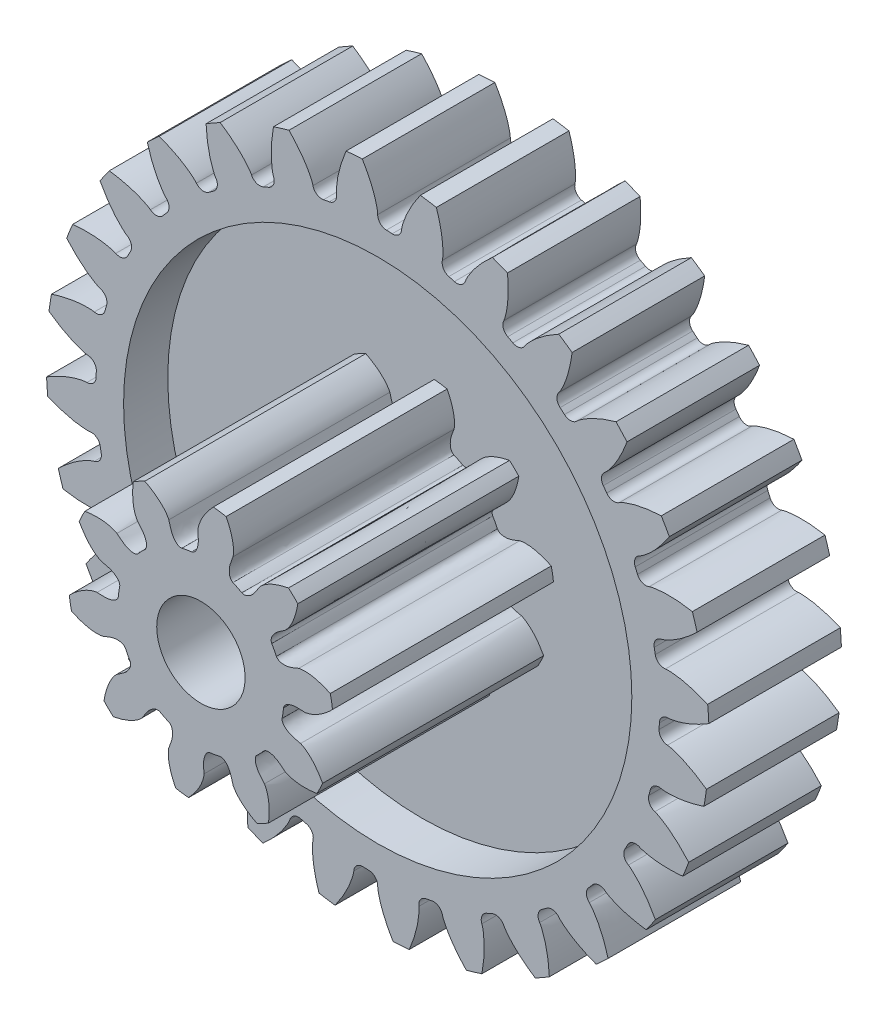
SolidWorks part; units mm, degrees
ref_plane "Plan de face" through (0, 0, 0) normal (0, 0, 1) x (1, 0, 0)
ref_plane "Plan de dessus" through (0, 0, 0) normal (0, 1, 0) x (1, 0, 0)
ref_plane "Plan de droite" through (0, 0, 0) normal (1, 0, 0) x (0, 0, -1)
sketch "Esquisse1" plane through (0, 0, 0) normal (0, 0, 1) x (1, 0, 0)
  arc A0 (7.4919, 0.3492) -> (7.4659, 0.7148) centre (0, 0) ccw
  arc A1 (7.2263, 2.0075) -> (7.1196, 2.3582) centre (0, 0) ccw
  arc A2 (6.5984, 3.5652) -> (6.4164, 3.8833) centre (0, 0) ccw
  arc A3 (5.6397, 4.9441) -> (5.3914, 5.2137) centre (0, 0) ccw
  arc A4 (4.3981, 6.0751) -> (4.0961, 6.2827) centre (0, 0) ccw
  arc A5 (2.936, 6.9014) -> (2.5953, 7.0366) centre (0, 0) ccw
  arc A6 (1.3267, 7.3817) -> (0.9645, 7.4377) centre (0, 0) ccw
  arc A7 (-0.3492, 7.4919) -> (-0.7148, 7.4659) centre (0, 0) ccw
  arc A8 (-2.0075, 7.2263) -> (-2.3582, 7.1196) centre (0, 0) ccw
  arc A9 (-3.5652, 6.5984) -> (-3.8833, 6.4164) centre (0, 0) ccw
  arc A10 (-4.9441, 5.6397) -> (-5.2137, 5.3914) centre (0, 0) ccw
  arc A11 (-6.0751, 4.3981) -> (-6.2827, 4.0961) centre (0, 0) ccw
  arc A12 (-6.9014, 2.936) -> (-7.0366, 2.5953) centre (0, 0) ccw
  arc A13 (-7.3817, 1.3267) -> (-7.4377, 0.9645) centre (0, 0) ccw
  arc A14 (-7.4919, -0.3492) -> (-7.4659, -0.7148) centre (0, 0) ccw
  arc A15 (-7.2263, -2.0075) -> (-7.1196, -2.3582) centre (0, 0) ccw
  arc A16 (-6.5984, -3.5652) -> (-6.4164, -3.8833) centre (0, 0) ccw
  arc A17 (-5.6397, -4.9441) -> (-5.3914, -5.2137) centre (0, 0) ccw
  arc A18 (-4.3981, -6.0751) -> (-4.0961, -6.2827) centre (0, 0) ccw
  arc A19 (-2.936, -6.9014) -> (-2.5953, -7.0366) centre (0, 0) ccw
  arc A20 (-1.3267, -7.3817) -> (-0.9645, -7.4377) centre (0, 0) ccw
  arc A21 (0.3492, -7.4919) -> (0.7148, -7.4659) centre (0, 0) ccw
  arc A22 (2.0075, -7.2263) -> (2.3582, -7.1196) centre (0, 0) ccw
  arc A23 (3.5652, -6.5984) -> (3.8833, -6.4164) centre (0, 0) ccw
  arc A24 (4.9441, -5.6397) -> (5.2137, -5.3914) centre (0, 0) ccw
  arc A25 (6.0751, -4.3981) -> (6.2827, -4.0961) centre (0, 0) ccw
  arc A26 (6.9014, -2.936) -> (7.0366, -2.5953) centre (0, 0) ccw
  arc A27 (7.3817, -1.3267) -> (7.4377, -0.9645) centre (0, 0) ccw
  arc A28 (6.578, 0) -> (6.372, -0.1967) centre (6.5749, -0.203) ccw
  arc A29 (6.3665, -0.3283) -> (6.5557, -0.5413) centre (6.5693, -0.3388) ccw
  arc A30 (6.3665, -0.3283) -> (6.372, -0.1967) centre (0, 0) ccw
  arc A31 (6.4131, 1.4637) -> (6.256, 1.2261) centre (6.4552, 1.2652) ccw
  arc A32 (6.28, 1.0966) -> (6.5118, 0.9311) centre (6.4799, 1.1315) ccw
  arc A33 (6.28, 1.0966) -> (6.256, 1.2261) centre (0, 0) ccw
  arc A34 (5.9266, 2.8541) -> (5.8263, 2.5875) centre (6.0118, 2.6699) ccw
  arc A35 (5.8785, 2.4666) -> (6.1413, 2.3567) centre (6.0657, 2.5451) ccw
  arc A36 (5.8785, 2.4666) -> (5.8263, 2.5875) centre (0, 0) ccw
  arc A37 (5.1429, 4.1013) -> (5.1045, 3.8191) centre (5.267, 3.9407) ccw
  arc A38 (5.1823, 3.7128) -> (5.4629, 3.6642) centre (5.3473, 3.831) ccw
  arc A39 (5.1823, 3.7128) -> (5.1045, 3.8191) centre (0, 0) ccw
  arc A40 (4.1013, 5.1429) -> (4.1267, 4.8592) centre (4.2581, 5.0139) ccw
  arc A41 (4.2261, 4.7729) -> (4.5106, 4.788) centre (4.3607, 4.9249) ccw
  arc A42 (4.2261, 4.7729) -> (4.1267, 4.8592) centre (0, 0) ccw
  arc A43 (2.8541, 5.9266) -> (2.9419, 5.6556) centre (3.0356, 5.8357) ccw
  arc A44 (3.0581, 5.5936) -> (3.3321, 5.6716) centre (3.1555, 5.7717) ccw
  arc A45 (3.0581, 5.5936) -> (2.9419, 5.6556) centre (0, 0) ccw
  arc A46 (1.4637, 6.4131) -> (1.6097, 6.1684) centre (1.6609, 6.3649) ccw
  arc A47 (1.7368, 6.1339) -> (1.9865, 6.2709) centre (1.7921, 6.3292) ccw
  arc A48 (1.7368, 6.1339) -> (1.6097, 6.1684) centre (0, 0) ccw
  arc A49 (0, 6.578) -> (0.1967, 6.372) centre (0.203, 6.5749) ccw
  arc A50 (0.3283, 6.3665) -> (0.5413, 6.5557) centre (0.3388, 6.5693) ccw
  arc A51 (0.3283, 6.3665) -> (0.1967, 6.372) centre (0, 0) ccw
  arc A52 (-1.4637, 6.4131) -> (-1.2261, 6.256) centre (-1.2652, 6.4552) ccw
  arc A53 (-1.0966, 6.28) -> (-0.9311, 6.5118) centre (-1.1315, 6.4799) ccw
  arc A54 (-1.0966, 6.28) -> (-1.2261, 6.256) centre (0, 0) ccw
  arc A55 (-2.8541, 5.9266) -> (-2.5875, 5.8263) centre (-2.6699, 6.0118) ccw
  arc A56 (-2.4666, 5.8785) -> (-2.3567, 6.1413) centre (-2.5451, 6.0657) ccw
  arc A57 (-2.4666, 5.8785) -> (-2.5875, 5.8263) centre (0, 0) ccw
  arc A58 (-4.1013, 5.1429) -> (-3.8191, 5.1045) centre (-3.9407, 5.267) ccw
  arc A59 (-3.7128, 5.1823) -> (-3.6642, 5.4629) centre (-3.831, 5.3473) ccw
  arc A60 (-3.7128, 5.1823) -> (-3.8191, 5.1045) centre (0, 0) ccw
  arc A61 (-5.1429, 4.1013) -> (-4.8592, 4.1267) centre (-5.0139, 4.2581) ccw
  arc A62 (-4.7729, 4.2261) -> (-4.788, 4.5106) centre (-4.9249, 4.3607) ccw
  arc A63 (-4.7729, 4.2261) -> (-4.8592, 4.1267) centre (0, 0) ccw
  arc A64 (-5.9266, 2.8541) -> (-5.6556, 2.9419) centre (-5.8357, 3.0356) ccw
  arc A65 (-5.5936, 3.0581) -> (-5.6716, 3.3321) centre (-5.7717, 3.1555) ccw
  arc A66 (-5.5936, 3.0581) -> (-5.6556, 2.9419) centre (0, 0) ccw
  arc A67 (-6.4131, 1.4637) -> (-6.1684, 1.6097) centre (-6.3649, 1.6609) ccw
  arc A68 (-6.1339, 1.7368) -> (-6.2709, 1.9865) centre (-6.3292, 1.7921) ccw
  arc A69 (-6.1339, 1.7368) -> (-6.1684, 1.6097) centre (0, 0) ccw
  arc A70 (-6.578, 0) -> (-6.372, 0.1967) centre (-6.5749, 0.203) ccw
  arc A71 (-6.3665, 0.3283) -> (-6.5557, 0.5413) centre (-6.5693, 0.3388) ccw
  arc A72 (-6.3665, 0.3283) -> (-6.372, 0.1967) centre (0, 0) ccw
  arc A73 (-6.4131, -1.4637) -> (-6.256, -1.2261) centre (-6.4552, -1.2652) ccw
  arc A74 (-6.28, -1.0966) -> (-6.5118, -0.9311) centre (-6.4799, -1.1315) ccw
  arc A75 (-6.28, -1.0966) -> (-6.256, -1.2261) centre (0, 0) ccw
  arc A76 (-5.9266, -2.8541) -> (-5.8263, -2.5875) centre (-6.0118, -2.6699) ccw
  arc A77 (-5.8785, -2.4666) -> (-6.1413, -2.3567) centre (-6.0657, -2.5451) ccw
  arc A78 (-5.8785, -2.4666) -> (-5.8263, -2.5875) centre (0, 0) ccw
  arc A79 (-5.1429, -4.1013) -> (-5.1045, -3.8191) centre (-5.267, -3.9407) ccw
  arc A80 (-5.1823, -3.7128) -> (-5.4629, -3.6642) centre (-5.3473, -3.831) ccw
  arc A81 (-5.1823, -3.7128) -> (-5.1045, -3.8191) centre (0, 0) ccw
  arc A82 (-4.1013, -5.1429) -> (-4.1267, -4.8592) centre (-4.2581, -5.0139) ccw
  arc A83 (-4.2261, -4.7729) -> (-4.5106, -4.788) centre (-4.3607, -4.9249) ccw
  arc A84 (-4.2261, -4.7729) -> (-4.1267, -4.8592) centre (0, 0) ccw
  arc A85 (-2.8541, -5.9266) -> (-2.9419, -5.6556) centre (-3.0356, -5.8357) ccw
  arc A86 (-3.0581, -5.5936) -> (-3.3321, -5.6716) centre (-3.1555, -5.7717) ccw
  arc A87 (-3.0581, -5.5936) -> (-2.9419, -5.6556) centre (0, 0) ccw
  arc A88 (-1.4637, -6.4131) -> (-1.6097, -6.1684) centre (-1.6609, -6.3649) ccw
  arc A89 (-1.7368, -6.1339) -> (-1.9865, -6.2709) centre (-1.7921, -6.3292) ccw
  arc A90 (-1.7368, -6.1339) -> (-1.6097, -6.1684) centre (0, 0) ccw
  arc A91 (0, -6.578) -> (-0.1967, -6.372) centre (-0.203, -6.5749) ccw
  arc A92 (-0.3283, -6.3665) -> (-0.5413, -6.5557) centre (-0.3388, -6.5693) ccw
  arc A93 (-0.3283, -6.3665) -> (-0.1967, -6.372) centre (0, 0) ccw
  arc A94 (1.4637, -6.4131) -> (1.2261, -6.256) centre (1.2652, -6.4552) ccw
  arc A95 (1.0966, -6.28) -> (0.9311, -6.5118) centre (1.1315, -6.4799) ccw
  arc A96 (1.0966, -6.28) -> (1.2261, -6.256) centre (0, 0) ccw
  arc A97 (2.8541, -5.9266) -> (2.5875, -5.8263) centre (2.6699, -6.0118) ccw
  arc A98 (2.4666, -5.8785) -> (2.3567, -6.1413) centre (2.5451, -6.0657) ccw
  arc A99 (2.4666, -5.8785) -> (2.5875, -5.8263) centre (0, 0) ccw
  arc A100 (4.1013, -5.1429) -> (3.8191, -5.1045) centre (3.9407, -5.267) ccw
  arc A101 (3.7128, -5.1823) -> (3.6642, -5.4629) centre (3.831, -5.3473) ccw
  arc A102 (3.7128, -5.1823) -> (3.8191, -5.1045) centre (0, 0) ccw
  arc A103 (5.1429, -4.1013) -> (4.8592, -4.1267) centre (5.0139, -4.2581) ccw
  arc A104 (4.7729, -4.2261) -> (4.788, -4.5106) centre (4.9249, -4.3607) ccw
  arc A105 (4.7729, -4.2261) -> (4.8592, -4.1267) centre (0, 0) ccw
  arc A106 (5.9266, -2.8541) -> (5.6556, -2.9419) centre (5.8357, -3.0356) ccw
  arc A107 (5.5936, -3.0581) -> (5.6716, -3.3321) centre (5.7717, -3.1555) ccw
  arc A108 (5.5936, -3.0581) -> (5.6556, -2.9419) centre (0, 0) ccw
  arc A109 (6.4131, -1.4637) -> (6.1684, -1.6097) centre (6.3649, -1.6609) ccw
  arc A110 (6.1339, -1.7368) -> (6.2709, -1.9865) centre (6.3292, -1.7921) ccw
  arc A111 (6.1339, -1.7368) -> (6.1684, -1.6097) centre (0, 0) ccw
  circle A112 centre (0, 0) radius 1
  spline S0 degree 3 poles (6.578, 0) (6.6119, 0) (6.7559, 0.0236) (6.9849, 0.0917) (7.2537, 0.2125) (7.4145, 0.3021) (7.4919, 0.3492) knots 0 0 0 0 0.1017 0.434977 0.714423 0.984887 0.984887 0.984887 0.984887
  spline S1 degree 3 poles (6.5118, 0.9311) (6.5453, 0.9359) (6.6912, 0.9329) (6.9276, 0.8979) (7.2108, 0.8163) (7.3826, 0.7504) (7.4659, 0.7148) knots 0 0 0 0 0.1017 0.434977 0.714423 0.984887 0.984887 0.984887 0.984887
  spline S2 degree 3 poles (6.4131, 1.4637) (6.4461, 1.4713) (6.5813, 1.5263) (6.7894, 1.6437) (7.0245, 1.8213) (7.1614, 1.9444) (7.2263, 2.0075) knots 0 0 0 0 0.1017 0.434977 0.714423 0.984887 0.984887 0.984887 0.984887
  spline S3 degree 3 poles (6.1413, 2.3567) (6.173, 2.3689) (6.3159, 2.3984) (6.5541, 2.4169) (6.8483, 2.4004) (7.0306, 2.3743) (7.1196, 2.3582) knots 0 0 0 0 0.1017 0.434977 0.714423 0.984887 0.984887 0.984887 0.984887
  spline S4 degree 3 poles (5.9266, 2.8541) (5.9571, 2.8688) (6.0766, 2.9525) (6.2534, 3.1132) (6.4431, 3.3388) (6.5492, 3.4892) (6.5984, 3.5652) knots 0 0 0 0 0.1017 0.434977 0.714423 0.984887 0.984887 0.984887 0.984887
  spline S5 degree 3 poles (5.4629, 3.6642) (5.4911, 3.6831) (5.6238, 3.7437) (5.8519, 3.8147) (6.1425, 3.8641) (6.3259, 3.8793) (6.4164, 3.8833) knots 0 0 0 0 0.1017 0.434977 0.714423 0.984887 0.984887 0.984887 0.984887
  spline S6 degree 3 poles (5.1429, 4.1013) (5.1694, 4.1225) (5.2673, 4.2307) (5.4039, 4.4267) (5.5387, 4.6888) (5.6085, 4.8591) (5.6397, 4.9441) knots 0 0 0 0 0.1017 0.434977 0.714423 0.984887 0.984887 0.984887 0.984887
  spline S7 degree 3 poles (4.5106, 4.788) (4.5339, 4.8126) (4.6498, 4.9013) (4.8563, 5.0213) (5.1286, 5.134) (5.3041, 5.1897) (5.3914, 5.2137) knots 0 0 0 0 0.1017 0.434977 0.714423 0.984887 0.984887 0.984887 0.984887
  spline S8 degree 3 poles (4.1013, 5.1429) (4.1225, 5.1694) (4.1938, 5.2967) (4.2833, 5.5182) (4.3564, 5.8037) (4.3867, 5.9853) (4.3981, 6.0751) knots 0 0 0 0 0.1017 0.434977 0.714423 0.984887 0.984887 0.984887 0.984887
  spline S9 degree 3 poles (3.3321, 5.6716) (3.3493, 5.7008) (3.4426, 5.8131) (3.6173, 5.976) (3.8576, 6.1465) (4.0163, 6.2398) (4.0961, 6.2827) knots 0 0 0 0 0.1017 0.434977 0.714423 0.984887 0.984887 0.984887 0.984887
  spline S10 degree 3 poles (2.8541, 5.9266) (2.8688, 5.9571) (2.91, 6.0971) (2.948, 6.333) (2.9558, 6.6276) (2.9448, 6.8113) (2.936, 6.9014) knots 0 0 0 0 0.1017 0.434977 0.714423 0.984887 0.984887 0.984887 0.984887
  spline S11 degree 3 poles (1.9865, 6.2709) (1.9967, 6.3032) (2.0627, 6.4334) (2.1968, 6.6311) (2.3932, 6.8508) (2.5271, 6.9771) (2.5953, 7.0366) knots 0 0 0 0 0.1017 0.434977 0.714423 0.984887 0.984887 0.984887 0.984887
  spline S12 degree 3 poles (1.4637, 6.4131) (1.4713, 6.4461) (1.4803, 6.5918) (1.4649, 6.8302) (1.4069, 7.1191) (1.3553, 7.2958) (1.3267, 7.3817) knots 0 0 0 0 0.1017 0.434977 0.714423 0.984887 0.984887 0.984887 0.984887
  spline S13 degree 3 poles (0.5413, 6.5557) (0.5441, 6.5895) (0.5794, 6.7311) (0.6661, 6.9537) (0.8087, 7.2116) (0.9112, 7.3645) (0.9645, 7.4377) knots 0 0 0 0 0.1017 0.434977 0.714423 0.984887 0.984887 0.984887 0.984887
  spline S14 degree 3 poles (0, 6.578) (0, 6.6119) (-0.0236, 6.7559) (-0.0917, 6.9849) (-0.2125, 7.2537) (-0.3021, 7.4145) (-0.3492, 7.4919) knots 0 0 0 0 0.1017 0.434977 0.714423 0.984887 0.984887 0.984887 0.984887
  spline S15 degree 3 poles (-0.9311, 6.5118) (-0.9359, 6.5453) (-0.9329, 6.6912) (-0.8979, 6.9276) (-0.8163, 7.2108) (-0.7504, 7.3826) (-0.7148, 7.4659) knots 0 0 0 0 0.1017 0.434977 0.714423 0.984887 0.984887 0.984887 0.984887
  spline S16 degree 3 poles (-1.4637, 6.4131) (-1.4713, 6.4461) (-1.5263, 6.5813) (-1.6437, 6.7894) (-1.8213, 7.0245) (-1.9444, 7.1614) (-2.0075, 7.2263) knots 0 0 0 0 0.1017 0.434977 0.714423 0.984887 0.984887 0.984887 0.984887
  spline S17 degree 3 poles (-2.3567, 6.1413) (-2.3689, 6.173) (-2.3984, 6.3159) (-2.4169, 6.5541) (-2.4004, 6.8483) (-2.3743, 7.0306) (-2.3582, 7.1196) knots 0 0 0 0 0.1017 0.434977 0.714423 0.984887 0.984887 0.984887 0.984887
  spline S18 degree 3 poles (-2.8541, 5.9266) (-2.8688, 5.9571) (-2.9525, 6.0766) (-3.1132, 6.2534) (-3.3388, 6.4431) (-3.4892, 6.5492) (-3.5652, 6.5984) knots 0 0 0 0 0.1017 0.434977 0.714423 0.984887 0.984887 0.984887 0.984887
  spline S19 degree 3 poles (-3.6642, 5.4629) (-3.6831, 5.4911) (-3.7437, 5.6238) (-3.8147, 5.8519) (-3.8641, 6.1425) (-3.8793, 6.3259) (-3.8833, 6.4164) knots 0 0 0 0 0.1017 0.434977 0.714423 0.984887 0.984887 0.984887 0.984887
  spline S20 degree 3 poles (-4.1013, 5.1429) (-4.1225, 5.1694) (-4.2307, 5.2673) (-4.4267, 5.4039) (-4.6888, 5.5387) (-4.8591, 5.6085) (-4.9441, 5.6397) knots 0 0 0 0 0.1017 0.434977 0.714423 0.984887 0.984887 0.984887 0.984887
  spline S21 degree 3 poles (-4.788, 4.5106) (-4.8126, 4.5339) (-4.9013, 4.6498) (-5.0213, 4.8563) (-5.134, 5.1286) (-5.1897, 5.3041) (-5.2137, 5.3914) knots 0 0 0 0 0.1017 0.434977 0.714423 0.984887 0.984887 0.984887 0.984887
  spline S22 degree 3 poles (-5.1429, 4.1013) (-5.1694, 4.1225) (-5.2967, 4.1938) (-5.5182, 4.2833) (-5.8037, 4.3564) (-5.9853, 4.3867) (-6.0751, 4.3981) knots 0 0 0 0 0.1017 0.434977 0.714423 0.984887 0.984887 0.984887 0.984887
  spline S23 degree 3 poles (-5.6716, 3.3321) (-5.7008, 3.3493) (-5.8131, 3.4426) (-5.976, 3.6173) (-6.1465, 3.8576) (-6.2398, 4.0163) (-6.2827, 4.0961) knots 0 0 0 0 0.1017 0.434977 0.714423 0.984887 0.984887 0.984887 0.984887
  spline S24 degree 3 poles (-5.9266, 2.8541) (-5.9571, 2.8688) (-6.0971, 2.91) (-6.333, 2.948) (-6.6276, 2.9558) (-6.8113, 2.9448) (-6.9014, 2.936) knots 0 0 0 0 0.1017 0.434977 0.714423 0.984887 0.984887 0.984887 0.984887
  spline S25 degree 3 poles (-6.2709, 1.9865) (-6.3032, 1.9967) (-6.4334, 2.0627) (-6.6311, 2.1968) (-6.8508, 2.3932) (-6.9771, 2.5271) (-7.0366, 2.5953) knots 0 0 0 0 0.1017 0.434977 0.714423 0.984887 0.984887 0.984887 0.984887
  spline S26 degree 3 poles (-6.4131, 1.4637) (-6.4461, 1.4713) (-6.5918, 1.4803) (-6.8302, 1.4649) (-7.1191, 1.4069) (-7.2958, 1.3553) (-7.3817, 1.3267) knots 0 0 0 0 0.1017 0.434977 0.714423 0.984887 0.984887 0.984887 0.984887
  spline S27 degree 3 poles (-6.5557, 0.5413) (-6.5895, 0.5441) (-6.7311, 0.5794) (-6.9537, 0.6661) (-7.2116, 0.8087) (-7.3645, 0.9112) (-7.4377, 0.9645) knots 0 0 0 0 0.1017 0.434977 0.714423 0.984887 0.984887 0.984887 0.984887
  spline S28 degree 3 poles (-6.578, 0) (-6.6119, 0) (-6.7559, -0.0236) (-6.9849, -0.0917) (-7.2537, -0.2125) (-7.4145, -0.3021) (-7.4919, -0.3492) knots 0 0 0 0 0.1017 0.434977 0.714423 0.984887 0.984887 0.984887 0.984887
  spline S29 degree 3 poles (-6.5118, -0.9311) (-6.5453, -0.9359) (-6.6912, -0.9329) (-6.9276, -0.8979) (-7.2108, -0.8163) (-7.3826, -0.7504) (-7.4659, -0.7148) knots 0 0 0 0 0.1017 0.434977 0.714423 0.984887 0.984887 0.984887 0.984887
  spline S30 degree 3 poles (-6.4131, -1.4637) (-6.4461, -1.4713) (-6.5813, -1.5263) (-6.7894, -1.6437) (-7.0245, -1.8213) (-7.1614, -1.9444) (-7.2263, -2.0075) knots 0 0 0 0 0.1017 0.434977 0.714423 0.984887 0.984887 0.984887 0.984887
  spline S31 degree 3 poles (-6.1413, -2.3567) (-6.173, -2.3689) (-6.3159, -2.3984) (-6.5541, -2.4169) (-6.8483, -2.4004) (-7.0306, -2.3743) (-7.1196, -2.3582) knots 0 0 0 0 0.1017 0.434977 0.714423 0.984887 0.984887 0.984887 0.984887
  spline S32 degree 3 poles (-5.9266, -2.8541) (-5.9571, -2.8688) (-6.0766, -2.9525) (-6.2534, -3.1132) (-6.4431, -3.3388) (-6.5492, -3.4892) (-6.5984, -3.5652) knots 0 0 0 0 0.1017 0.434977 0.714423 0.984887 0.984887 0.984887 0.984887
  spline S33 degree 3 poles (-5.4629, -3.6642) (-5.4911, -3.6831) (-5.6238, -3.7437) (-5.8519, -3.8147) (-6.1425, -3.8641) (-6.3259, -3.8793) (-6.4164, -3.8833) knots 0 0 0 0 0.1017 0.434977 0.714423 0.984887 0.984887 0.984887 0.984887
  spline S34 degree 3 poles (-5.1429, -4.1013) (-5.1694, -4.1225) (-5.2673, -4.2307) (-5.4039, -4.4267) (-5.5387, -4.6888) (-5.6085, -4.8591) (-5.6397, -4.9441) knots 0 0 0 0 0.1017 0.434977 0.714423 0.984887 0.984887 0.984887 0.984887
  spline S35 degree 3 poles (-4.5106, -4.788) (-4.5339, -4.8126) (-4.6498, -4.9013) (-4.8563, -5.0213) (-5.1286, -5.134) (-5.3041, -5.1897) (-5.3914, -5.2137) knots 0 0 0 0 0.1017 0.434977 0.714423 0.984887 0.984887 0.984887 0.984887
  spline S36 degree 3 poles (-4.1013, -5.1429) (-4.1225, -5.1694) (-4.1938, -5.2967) (-4.2833, -5.5182) (-4.3564, -5.8037) (-4.3867, -5.9853) (-4.3981, -6.0751) knots 0 0 0 0 0.1017 0.434977 0.714423 0.984887 0.984887 0.984887 0.984887
  spline S37 degree 3 poles (-3.3321, -5.6716) (-3.3493, -5.7008) (-3.4426, -5.8131) (-3.6173, -5.976) (-3.8576, -6.1465) (-4.0163, -6.2398) (-4.0961, -6.2827) knots 0 0 0 0 0.1017 0.434977 0.714423 0.984887 0.984887 0.984887 0.984887
  spline S38 degree 3 poles (-2.8541, -5.9266) (-2.8688, -5.9571) (-2.91, -6.0971) (-2.948, -6.333) (-2.9558, -6.6276) (-2.9448, -6.8113) (-2.936, -6.9014) knots 0 0 0 0 0.1017 0.434977 0.714423 0.984887 0.984887 0.984887 0.984887
  spline S39 degree 3 poles (-1.9865, -6.2709) (-1.9967, -6.3032) (-2.0627, -6.4334) (-2.1968, -6.6311) (-2.3932, -6.8508) (-2.5271, -6.9771) (-2.5953, -7.0366) knots 0 0 0 0 0.1017 0.434977 0.714423 0.984887 0.984887 0.984887 0.984887
  spline S40 degree 3 poles (-1.4637, -6.4131) (-1.4713, -6.4461) (-1.4803, -6.5918) (-1.4649, -6.8302) (-1.4069, -7.1191) (-1.3553, -7.2958) (-1.3267, -7.3817) knots 0 0 0 0 0.1017 0.434977 0.714423 0.984887 0.984887 0.984887 0.984887
  spline S41 degree 3 poles (-0.5413, -6.5557) (-0.5441, -6.5895) (-0.5794, -6.7311) (-0.6661, -6.9537) (-0.8087, -7.2116) (-0.9112, -7.3645) (-0.9645, -7.4377) knots 0 0 0 0 0.1017 0.434977 0.714423 0.984887 0.984887 0.984887 0.984887
  spline S42 degree 3 poles (0, -6.578) (0, -6.6119) (0.0236, -6.7559) (0.0917, -6.9849) (0.2125, -7.2537) (0.3021, -7.4145) (0.3492, -7.4919) knots 0 0 0 0 0.1017 0.434977 0.714423 0.984887 0.984887 0.984887 0.984887
  spline S43 degree 3 poles (0.9311, -6.5118) (0.9359, -6.5453) (0.9329, -6.6912) (0.8979, -6.9276) (0.8163, -7.2108) (0.7504, -7.3826) (0.7148, -7.4659) knots 0 0 0 0 0.1017 0.434977 0.714423 0.984887 0.984887 0.984887 0.984887
  spline S44 degree 3 poles (1.4637, -6.4131) (1.4713, -6.4461) (1.5263, -6.5813) (1.6437, -6.7894) (1.8213, -7.0245) (1.9444, -7.1614) (2.0075, -7.2263) knots 0 0 0 0 0.1017 0.434977 0.714423 0.984887 0.984887 0.984887 0.984887
  spline S45 degree 3 poles (2.3567, -6.1413) (2.3689, -6.173) (2.3984, -6.3159) (2.4169, -6.5541) (2.4004, -6.8483) (2.3743, -7.0306) (2.3582, -7.1196) knots 0 0 0 0 0.1017 0.434977 0.714423 0.984887 0.984887 0.984887 0.984887
  spline S46 degree 3 poles (2.8541, -5.9266) (2.8688, -5.9571) (2.9525, -6.0766) (3.1132, -6.2534) (3.3388, -6.4431) (3.4892, -6.5492) (3.5652, -6.5984) knots 0 0 0 0 0.1017 0.434977 0.714423 0.984887 0.984887 0.984887 0.984887
  spline S47 degree 3 poles (3.6642, -5.4629) (3.6831, -5.4911) (3.7437, -5.6238) (3.8147, -5.8519) (3.8641, -6.1425) (3.8793, -6.3259) (3.8833, -6.4164) knots 0 0 0 0 0.1017 0.434977 0.714423 0.984887 0.984887 0.984887 0.984887
  spline S48 degree 3 poles (4.1013, -5.1429) (4.1225, -5.1694) (4.2307, -5.2673) (4.4267, -5.4039) (4.6888, -5.5387) (4.8591, -5.6085) (4.9441, -5.6397) knots 0 0 0 0 0.1017 0.434977 0.714423 0.984887 0.984887 0.984887 0.984887
  spline S49 degree 3 poles (4.788, -4.5106) (4.8126, -4.5339) (4.9013, -4.6498) (5.0213, -4.8563) (5.134, -5.1286) (5.1897, -5.3041) (5.2137, -5.3914) knots 0 0 0 0 0.1017 0.434977 0.714423 0.984887 0.984887 0.984887 0.984887
  spline S50 degree 3 poles (5.1429, -4.1013) (5.1694, -4.1225) (5.2967, -4.1938) (5.5182, -4.2833) (5.8037, -4.3564) (5.9853, -4.3867) (6.0751, -4.3981) knots 0 0 0 0 0.1017 0.434977 0.714423 0.984887 0.984887 0.984887 0.984887
  spline S51 degree 3 poles (5.6716, -3.3321) (5.7008, -3.3493) (5.8131, -3.4426) (5.976, -3.6173) (6.1465, -3.8576) (6.2398, -4.0163) (6.2827, -4.0961) knots 0 0 0 0 0.1017 0.434977 0.714423 0.984887 0.984887 0.984887 0.984887
  spline S52 degree 3 poles (5.9266, -2.8541) (5.9571, -2.8688) (6.0971, -2.91) (6.333, -2.948) (6.6276, -2.9558) (6.8113, -2.9448) (6.9014, -2.936) knots 0 0 0 0 0.1017 0.434977 0.714423 0.984887 0.984887 0.984887 0.984887
  spline S53 degree 3 poles (6.2709, -1.9865) (6.3032, -1.9967) (6.4334, -2.0627) (6.6311, -2.1968) (6.8508, -2.3932) (6.9771, -2.5271) (7.0366, -2.5953) knots 0 0 0 0 0.1017 0.434977 0.714423 0.984887 0.984887 0.984887 0.984887
  spline S54 degree 3 poles (6.4131, -1.4637) (6.4461, -1.4713) (6.5918, -1.4803) (6.8302, -1.4649) (7.1191, -1.4069) (7.2958, -1.3553) (7.3817, -1.3267) knots 0 0 0 0 0.1017 0.434977 0.714423 0.984887 0.984887 0.984887 0.984887
  spline S55 degree 3 poles (6.5557, -0.5413) (6.5895, -0.5441) (6.7311, -0.5794) (6.9537, -0.6661) (7.2116, -0.8087) (7.3645, -0.9112) (7.4377, -0.9645) knots 0 0 0 0 0.1017 0.434977 0.714423 0.984887 0.984887 0.984887 0.984887
  dimension "D1" = 2
extrude "Boss.-Extru.1" add sketch "Esquisse1" along normal blind 3
sketch "Esquisse2" plane through (0, 0, 3) normal (0, 0, 1) x (1, 0, 0)
  circle A0 centre (0, 0) radius 5.75
  dimension "D1" = 11.5
extrude "Enlèv. mat.-Extru.1" cut sketch "Esquisse2" against normal blind 1
sketch "Esquisse3" plane through (0, 0, 2) normal (0, 0, 1) x (1, 0, 0)
  arc A0 (2.9773, 0.3683) -> (2.9271, 0.6573) centre (0, 0) ccw
  arc A1 (2.1922, 2.048) -> (1.9817, 2.2523) centre (0, 0) ccw
  arc A2 (0.5698, 2.9454) -> (0.2794, 2.987) centre (0, 0) ccw
  arc A3 (-1.2703, 2.7178) -> (-1.5297, 2.5807) centre (0, 0) ccw
  arc A4 (-2.6252, 1.4521) -> (-2.7544, 1.1887) centre (0, 0) ccw
  arc A5 (-2.9773, -0.3683) -> (-2.9271, -0.6573) centre (0, 0) ccw
  arc A6 (-2.1922, -2.048) -> (-1.9817, -2.2523) centre (0, 0) ccw
  arc A7 (-0.5698, -2.9454) -> (-0.2794, -2.987) centre (0, 0) ccw
  arc A8 (1.2703, -2.7178) -> (1.5297, -2.5807) centre (0, 0) ccw
  arc A9 (2.6252, -1.4521) -> (2.7544, -1.1887) centre (0, 0) ccw
  arc A10 (1.8368, -0.3764) -> (1.8687, -0.154) centre (0, 0) ccw
  arc A11 (1.7073, 0.7751) -> (1.6023, 0.9738) centre (0, 0) ccw
  arc A12 (0.9256, 1.6306) -> (0.7239, 1.7296) centre (0, 0) ccw
  arc A13 (-0.2096, 1.8632) -> (-0.431, 1.8248) centre (0, 0) ccw
  arc A14 (-1.2648, 1.3842) -> (-1.4213, 1.2229) centre (0, 0) ccw
  arc A15 (-1.8368, 0.3764) -> (-1.8687, 0.154) centre (0, 0) ccw
  arc A16 (-1.7073, -0.7751) -> (-1.6023, -0.9738) centre (0, 0) ccw
  arc A17 (-0.9256, -1.6306) -> (-0.7239, -1.7296) centre (0, 0) ccw
  arc A18 (0.2096, -1.8632) -> (0.431, -1.8248) centre (0, 0) ccw
  arc A19 (1.2648, -1.3842) -> (1.4213, -1.2229) centre (0, 0) ccw
  circle A20 centre (0, 0) radius 1 construction
  circle A21 centre (0, 0) radius 1
  spline S0 degree 3 poles (2.349, 0) (2.3611, 0) (2.4126, 0.0085) (2.4945, 0.0326) (2.6584, 0.1065) (2.823, 0.2207) (2.9394, 0.3292) (2.9773, 0.3683) knots 0 0 0 0 0.036251 0.155621 0.255291 0.575255 0.744085 0.744085 0.744085 0.744085
  spline S1 degree 3 poles (2.2114, 0.7921) (2.2228, 0.7962) (2.2741, 0.8056) (2.3594, 0.8105) (2.5386, 0.7962) (2.7321, 0.7442) (2.8782, 0.6813) (2.9271, 0.6573) knots 0 0 0 0 0.036251 0.155621 0.255291 0.575255 0.744085 0.744085 0.744085 0.744085
  spline S2 degree 3 poles (1.9004, 1.3807) (1.9102, 1.3878) (1.9469, 1.4249) (1.9989, 1.4926) (2.0881, 1.6487) (2.1541, 1.8379) (2.1845, 1.9941) (2.1922, 2.048) knots 0 0 0 0 0.036251 0.155621 0.255291 0.575255 0.744085 0.744085 0.744085 0.744085
  spline S3 degree 3 poles (1.3235, 1.9407) (1.3303, 1.9507) (1.3663, 1.9885) (1.4324, 2.0425) (1.5858, 2.1363) (1.7728, 2.2079) (1.9281, 2.243) (1.9817, 2.2523) knots 0 0 0 0 0.036251 0.155621 0.255291 0.575255 0.744085 0.744085 0.744085 0.744085
  spline S4 degree 3 poles (0.7259, 2.234) (0.7296, 2.2455) (0.7375, 2.2971) (0.7398, 2.3825) (0.7202, 2.5612) (0.6625, 2.753) (0.5952, 2.8973) (0.5698, 2.9454) knots 0 0 0 0 0.036251 0.155621 0.255291 0.575255 0.744085 0.744085 0.744085 0.744085
  spline S5 degree 3 poles (-0.07, 2.348) (-0.0704, 2.36) (-0.0634, 2.4118) (-0.0417, 2.4943) (0.0272, 2.6604) (0.1365, 2.8283) (0.2415, 2.9479) (0.2794, 2.987) knots 0 0 0 0 0.036251 0.155621 0.255291 0.575255 0.744085 0.744085 0.744085 0.744085
  spline S6 degree 3 poles (-0.7259, 2.234) (-0.7296, 2.2455) (-0.7536, 2.2919) (-0.8019, 2.3623) (-0.9228, 2.4954) (-1.0823, 2.6166) (-1.2215, 2.6938) (-1.2703, 2.7178) knots 0 0 0 0 0.036251 0.155621 0.255291 0.575255 0.744085 0.744085 0.744085 0.744085
  spline S7 degree 3 poles (-1.4367, 1.8584) (-1.4441, 1.8679) (-1.4689, 1.9139) (-1.4999, 1.9934) (-1.5417, 2.1683) (-1.552, 2.3684) (-1.5374, 2.5268) (-1.5297, 2.5807) knots 0 0 0 0 0.036251 0.155621 0.255291 0.575255 0.744085 0.744085 0.744085 0.744085
  spline S8 degree 3 poles (-1.9004, 1.3807) (-1.9102, 1.3878) (-1.9568, 1.4112) (-2.0373, 1.4398) (-2.2133, 1.4764) (-2.4136, 1.4808) (-2.5715, 1.4614) (-2.6252, 1.4521) knots 0 0 0 0 0.036251 0.155621 0.255291 0.575255 0.744085 0.744085 0.744085 0.744085
  spline S9 degree 3 poles (-2.2547, 0.659) (-2.2663, 0.6624) (-2.3133, 0.6849) (-2.3852, 0.7311) (-2.5218, 0.848) (-2.6477, 1.0038) (-2.729, 1.1406) (-2.7544, 1.1887) knots 0 0 0 0 0.036251 0.155621 0.255291 0.575255 0.744085 0.744085 0.744085 0.744085
  spline S10 degree 3 poles (-2.349, 0) (-2.3611, 0) (-2.4126, -0.0085) (-2.4945, -0.0326) (-2.6584, -0.1065) (-2.823, -0.2207) (-2.9394, -0.3292) (-2.9773, -0.3683) knots 0 0 0 0 0.036251 0.155621 0.255291 0.575255 0.744085 0.744085 0.744085 0.744085
  spline S11 degree 3 poles (-2.2114, -0.7921) (-2.2228, -0.7962) (-2.2741, -0.8056) (-2.3594, -0.8105) (-2.5386, -0.7962) (-2.7321, -0.7442) (-2.8782, -0.6813) (-2.9271, -0.6573) knots 0 0 0 0 0.036251 0.155621 0.255291 0.575255 0.744085 0.744085 0.744085 0.744085
  spline S12 degree 3 poles (-1.9004, -1.3807) (-1.9102, -1.3878) (-1.9469, -1.4249) (-1.9989, -1.4926) (-2.0881, -1.6487) (-2.1541, -1.8379) (-2.1845, -1.9941) (-2.1922, -2.048) knots 0 0 0 0 0.036251 0.155621 0.255291 0.575255 0.744085 0.744085 0.744085 0.744085
  spline S13 degree 3 poles (-1.3235, -1.9407) (-1.3303, -1.9507) (-1.3663, -1.9885) (-1.4324, -2.0425) (-1.5858, -2.1363) (-1.7728, -2.2079) (-1.9281, -2.243) (-1.9817, -2.2523) knots 0 0 0 0 0.036251 0.155621 0.255291 0.575255 0.744085 0.744085 0.744085 0.744085
  spline S14 degree 3 poles (-0.7259, -2.234) (-0.7296, -2.2455) (-0.7375, -2.2971) (-0.7398, -2.3825) (-0.7202, -2.5612) (-0.6625, -2.753) (-0.5952, -2.8973) (-0.5698, -2.9454) knots 0 0 0 0 0.036251 0.155621 0.255291 0.575255 0.744085 0.744085 0.744085 0.744085
  spline S15 degree 3 poles (0.07, -2.348) (0.0704, -2.36) (0.0634, -2.4118) (0.0417, -2.4943) (-0.0272, -2.6604) (-0.1365, -2.8283) (-0.2415, -2.9479) (-0.2794, -2.987) knots 0 0 0 0 0.036251 0.155621 0.255291 0.575255 0.744085 0.744085 0.744085 0.744085
  spline S16 degree 3 poles (0.7259, -2.234) (0.7296, -2.2455) (0.7536, -2.2919) (0.8019, -2.3623) (0.9228, -2.4954) (1.0823, -2.6166) (1.2215, -2.6938) (1.2703, -2.7178) knots 0 0 0 0 0.036251 0.155621 0.255291 0.575255 0.744085 0.744085 0.744085 0.744085
  spline S17 degree 3 poles (1.4367, -1.8584) (1.4441, -1.8679) (1.4689, -1.9139) (1.4999, -1.9934) (1.5417, -2.1683) (1.552, -2.3684) (1.5374, -2.5268) (1.5297, -2.5807) knots 0 0 0 0 0.036251 0.155621 0.255291 0.575255 0.744085 0.744085 0.744085 0.744085
  spline S18 degree 3 poles (1.9004, -1.3807) (1.9102, -1.3878) (1.9568, -1.4112) (2.0373, -1.4398) (2.2133, -1.4764) (2.4136, -1.4808) (2.5715, -1.4614) (2.6252, -1.4521) knots 0 0 0 0 0.036251 0.155621 0.255291 0.575255 0.744085 0.744085 0.744085 0.744085
  spline S19 degree 3 poles (2.2547, -0.659) (2.2663, -0.6624) (2.3133, -0.6849) (2.3852, -0.7311) (2.5218, -0.848) (2.6477, -1.0038) (2.729, -1.1406) (2.7544, -1.1887) knots 0 0 0 0 0.036251 0.155621 0.255291 0.575255 0.744085 0.744085 0.744085 0.744085
  spline S20 degree 3 poles (2.349, 0) (2.2648, 0) (2.1034, 0.0291) (1.8817, -0.0633) (1.8687, -0.154) knots 0 0 0 0 0.252618 0.527509 0.527509 0.527509 0.527509
  spline S21 degree 3 poles (2.2547, -0.659) (2.1739, -0.6353) (2.0108, -0.618) (1.8238, -0.4671) (1.8368, -0.3764) knots 0 0 0 0 0.252618 0.527509 0.527509 0.527509 0.527509
  spline S22 degree 3 poles (1.9004, 1.3807) (1.8323, 1.3312) (1.6846, 1.2599) (1.5595, 1.0548) (1.6023, 0.9738) knots 0 0 0 0 0.252618 0.527509 0.527509 0.527509 0.527509
  spline S23 degree 3 poles (2.2114, 0.7921) (2.1321, 0.7637) (1.99, 0.682) (1.7501, 0.6941) (1.7073, 0.7751) knots 0 0 0 0 0.252618 0.527509 0.527509 0.527509 0.527509
  spline S24 degree 3 poles (0.7259, 2.234) (0.6999, 2.1539) (0.6223, 2.0095) (0.6416, 1.77) (0.7239, 1.7296) knots 0 0 0 0 0.252618 0.527509 0.527509 0.527509 0.527509
  spline S25 degree 3 poles (1.3235, 1.9407) (1.276, 1.8711) (1.2091, 1.7214) (1.0079, 1.5902) (0.9256, 1.6306) knots 0 0 0 0 0.252618 0.527509 0.527509 0.527509 0.527509
  spline S26 degree 3 poles (-0.7259, 2.234) (-0.6999, 2.1539) (-0.6776, 1.9915) (-0.5213, 1.8091) (-0.431, 1.8248) knots 0 0 0 0 0.252618 0.527509 0.527509 0.527509 0.527509
  spline S27 degree 3 poles (-0.07, 2.348) (-0.0675, 2.2638) (-0.0336, 2.1034) (-0.1193, 1.8789) (-0.2096, 1.8632) knots 0 0 0 0 0.252618 0.527509 0.527509 0.527509 0.527509
  spline S28 degree 3 poles (-1.9004, 1.3807) (-1.8323, 1.3312) (-1.7188, 1.2128) (-1.4851, 1.1572) (-1.4213, 1.2229) knots 0 0 0 0 0.252618 0.527509 0.527509 0.527509 0.527509
  spline S29 degree 3 poles (-1.4367, 1.8584) (-1.3852, 1.7918) (-1.2635, 1.6819) (-1.2009, 1.4499) (-1.2648, 1.3842) knots 0 0 0 0 0.252618 0.527509 0.527509 0.527509 0.527509
  spline S30 degree 3 poles (-2.349, 0) (-2.2648, 0) (-2.1034, -0.0291) (-1.8817, 0.0633) (-1.8687, 0.154) knots 0 0 0 0 0.252618 0.527509 0.527509 0.527509 0.527509
  spline S31 degree 3 poles (-2.2547, 0.659) (-2.1739, 0.6353) (-2.0108, 0.618) (-1.8238, 0.4671) (-1.8368, 0.3764) knots 0 0 0 0 0.252618 0.527509 0.527509 0.527509 0.527509
  spline S32 degree 3 poles (-1.9004, -1.3807) (-1.8323, -1.3312) (-1.6846, -1.2599) (-1.5595, -1.0548) (-1.6023, -0.9738) knots 0 0 0 0 0.252618 0.527509 0.527509 0.527509 0.527509
  spline S33 degree 3 poles (-2.2114, -0.7921) (-2.1321, -0.7637) (-1.99, -0.682) (-1.7501, -0.6941) (-1.7073, -0.7751) knots 0 0 0 0 0.252618 0.527509 0.527509 0.527509 0.527509
  spline S34 degree 3 poles (-0.7259, -2.234) (-0.6999, -2.1539) (-0.6223, -2.0095) (-0.6416, -1.77) (-0.7239, -1.7296) knots 0 0 0 0 0.252618 0.527509 0.527509 0.527509 0.527509
  spline S35 degree 3 poles (-1.3235, -1.9407) (-1.276, -1.8711) (-1.2091, -1.7214) (-1.0079, -1.5902) (-0.9256, -1.6306) knots 0 0 0 0 0.252618 0.527509 0.527509 0.527509 0.527509
  spline S36 degree 3 poles (0.7259, -2.234) (0.6999, -2.1539) (0.6776, -1.9915) (0.5213, -1.8091) (0.431, -1.8248) knots 0 0 0 0 0.252618 0.527509 0.527509 0.527509 0.527509
  spline S37 degree 3 poles (0.07, -2.348) (0.0675, -2.2638) (0.0336, -2.1034) (0.1193, -1.8789) (0.2096, -1.8632) knots 0 0 0 0 0.252618 0.527509 0.527509 0.527509 0.527509
  spline S38 degree 3 poles (1.9004, -1.3807) (1.8323, -1.3312) (1.7188, -1.2128) (1.4851, -1.1572) (1.4213, -1.2229) knots 0 0 0 0 0.252618 0.527509 0.527509 0.527509 0.527509
  spline S39 degree 3 poles (1.4367, -1.8584) (1.3852, -1.7918) (1.2635, -1.6819) (1.2009, -1.4499) (1.2648, -1.3842) knots 0 0 0 0 0.252618 0.527509 0.527509 0.527509 0.527509
extrude "Boss.-Extru.2" add sketch "Esquisse3" along normal blind 5
